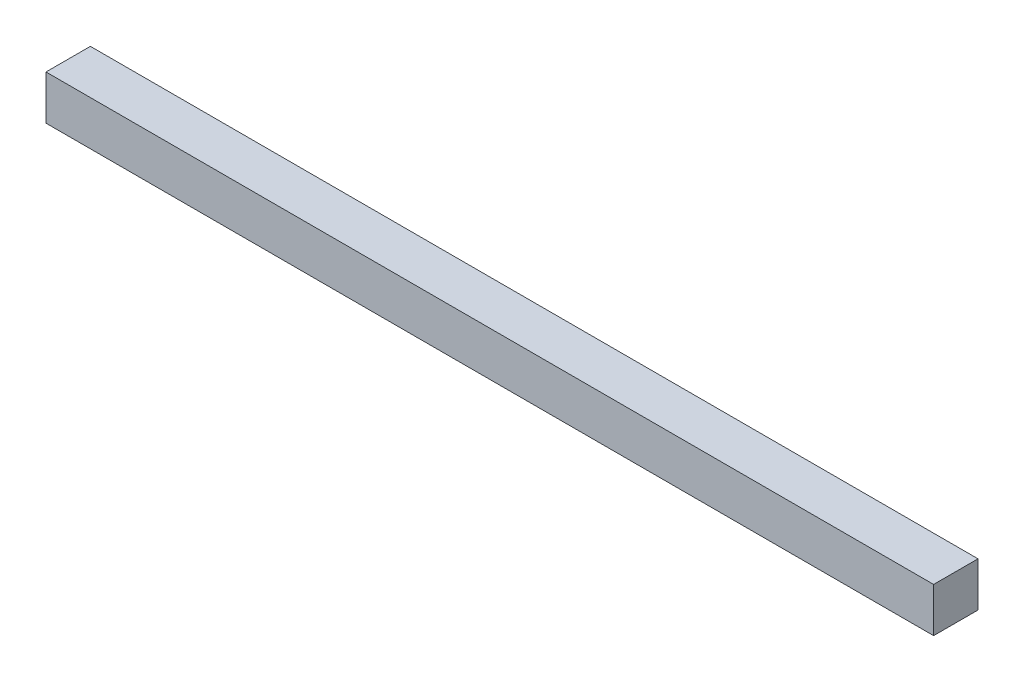
SolidWorks part; units mm, degrees
ref_plane "Спереди" through (0, 0, 0) normal (0, 0, 1) x (1, 0, 0)
ref_plane "Сверху" through (0, 0, 0) normal (0, 1, 0) x (1, 0, 0)
ref_plane "Справа" through (0, 0, 0) normal (1, 0, 0) x (0, 0, -1)
sketch "Эскиз1" plane through (0, 0, 0) normal (1, 0, 0) x (0, 0, -1)
  line L1 (16.5457, 22.6401) -> (-33.4543, 22.6401)
  line L2 (16.5457, 22.6401) -> (16.5457, -27.3599)
  line L3 (16.5457, -27.3599) -> (-33.4543, -27.3599)
  line L4 (-33.4543, 22.6401) -> (-33.4543, -27.3599)
extrude "Бобышка-Вытянуть1" add sketch "Эскиз1" along normal blind 1000
